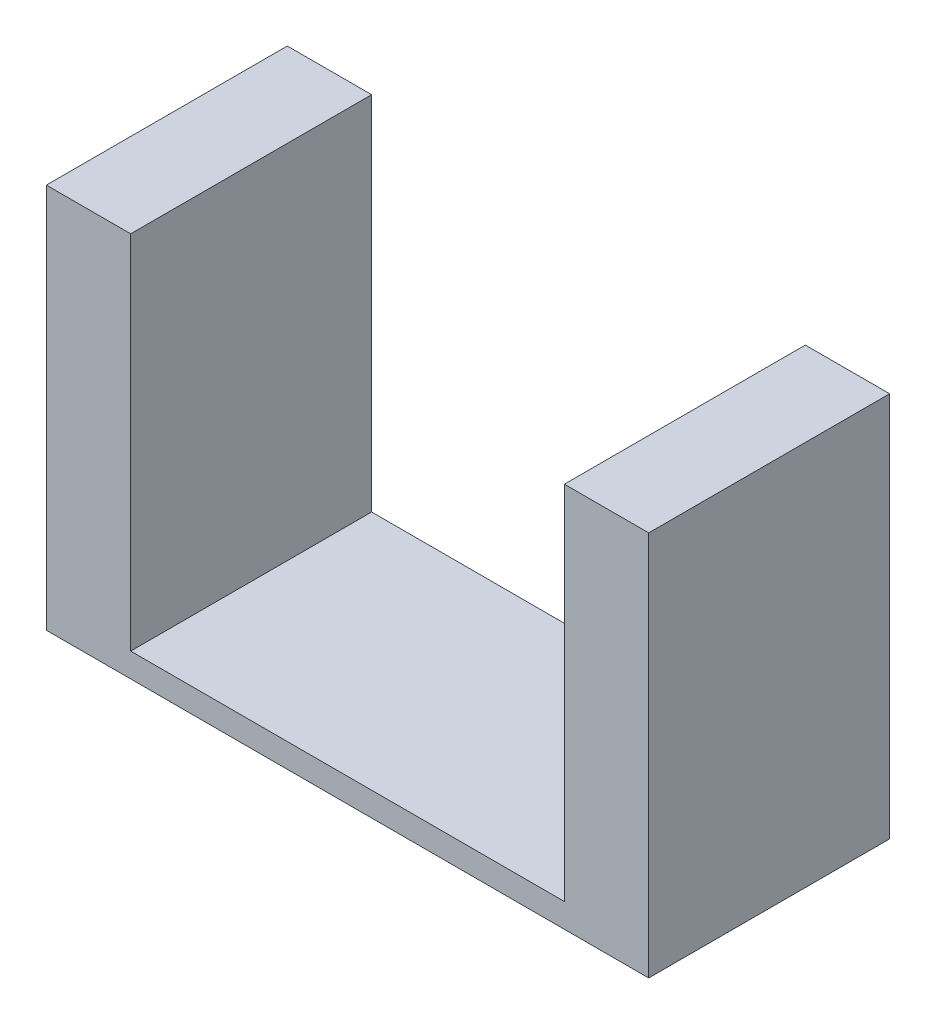
SolidWorks part; units mm, degrees
ref_plane "Front Plane" through (0, 0, 0) normal (0, 0, 1) x (1, 0, 0)
ref_plane "Top Plane" through (0, 0, 0) normal (0, 1, 0) x (1, 0, 0)
ref_plane "Right Plane" through (0, 0, 0) normal (1, 0, 0) x (0, 0, -1)
sketch "Sketch1" plane through (0, 0, 0) normal (0, 1, 0) x (1, 0, 0)
  line L1 (-25, 10) -> (25, 10)
  line L2 (-25, 10) -> (-25, -10)
  line L3 (-25, -10) -> (25, -10)
  line L4 (25, 10) -> (25, -10)
  line L5 (-25, 10) -> (25, -10) construction
  line L6 (-25, -10) -> (25, 10) construction
  point P0 (0, 0)
  dimension "D1" = 20
  dimension "D2" = 50
extrude "Boss-Extrude1" add sketch "Sketch1" along normal blind 2
sketch "Sketch2" plane through (0, 2, 0) normal (0, 1, 0) x (1, 0, 0)
  line L0 (-25, -10) -> (25, -10) construction
  line L1 (-25, 10) -> (-18, 10)
  line L2 (-25, 10) -> (-25, -10)
  line L3 (-25, -10) -> (-18, -10)
  line L4 (-18, 10) -> (-18, -10)
  line L6 (25, 10) -> (18, 10)
  line L7 (25, 10) -> (25, -10)
  line L8 (25, -10) -> (18, -10)
  line L9 (18, 10) -> (18, -10)
  dimension "D1" = 7
  dimension "D2" = 7
extrude "Boss-Extrude2" add sketch "Sketch2" along normal blind 30
